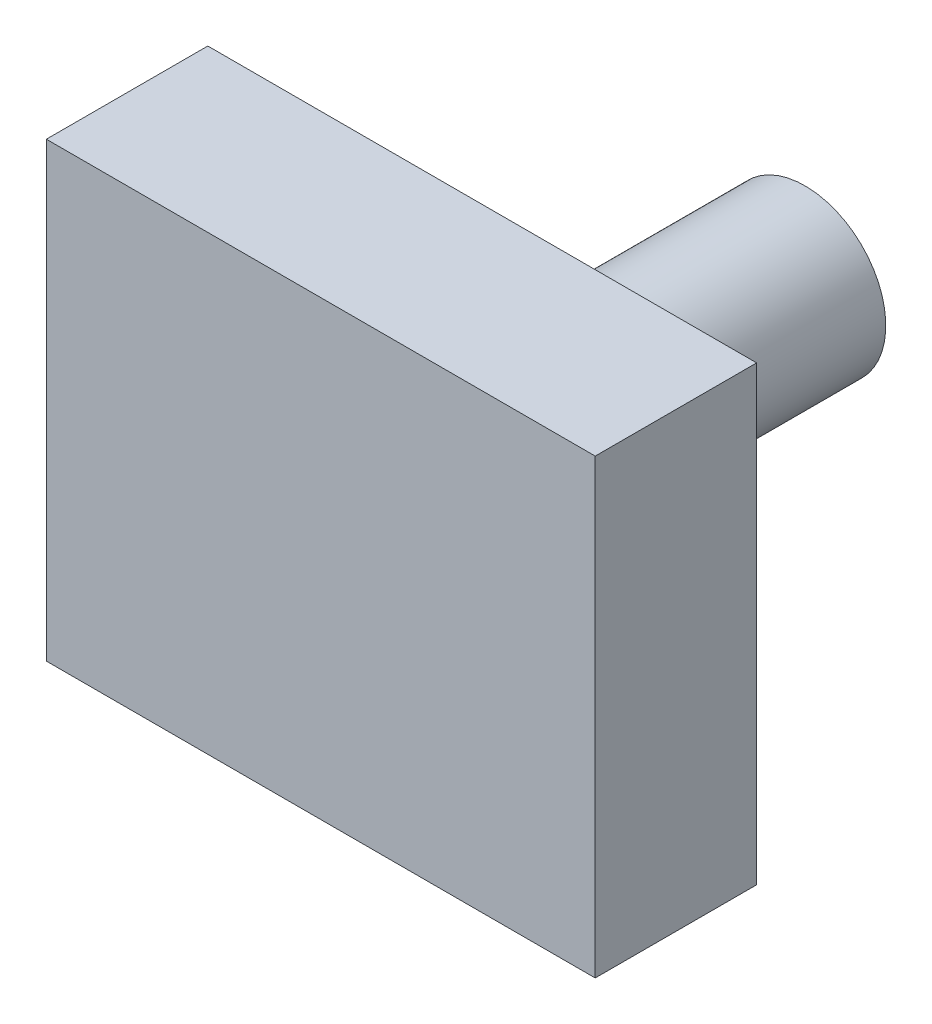
SolidWorks part; units mm, degrees
ref_plane "Plan de face" through (0, 0, 0) normal (0, 0, 1) x (1, 0, 0)
ref_plane "Plan de dessus" through (0, 0, 0) normal (0, 1, 0) x (1, 0, 0)
ref_plane "Plan de droite" through (0, 0, 0) normal (1, 0, 0) x (0, 0, -1)
sketch "Esquisse1" plane through (0, 0, 0) normal (0, 0, 1) x (1, 0, 0)
  line L1 (-8.5, 7) -> (8.5, 7)
  line L2 (-8.5, 7) -> (-8.5, -7)
  line L3 (-8.5, -7) -> (8.5, -7)
  line L4 (8.5, 7) -> (8.5, -7)
  line L5 (-8.5, 7) -> (8.5, -7) construction
  line L6 (-8.5, -7) -> (8.5, 7) construction
  point P0 (0, 0)
  dimension "D1" = 17
  dimension "D2" = 14
extrude "Boss.-Extru.1" add sketch "Esquisse1" along normal blind 5
sketch "Esquisse2" plane through (0, 0, 0) normal (0, 0, -1) x (-1, 0, 0)
  circle A0 centre (0, 0) radius 2.5
  dimension "D1" = 5
extrude "Boss.-Extru.2" add sketch "Esquisse2" along normal blind 10
